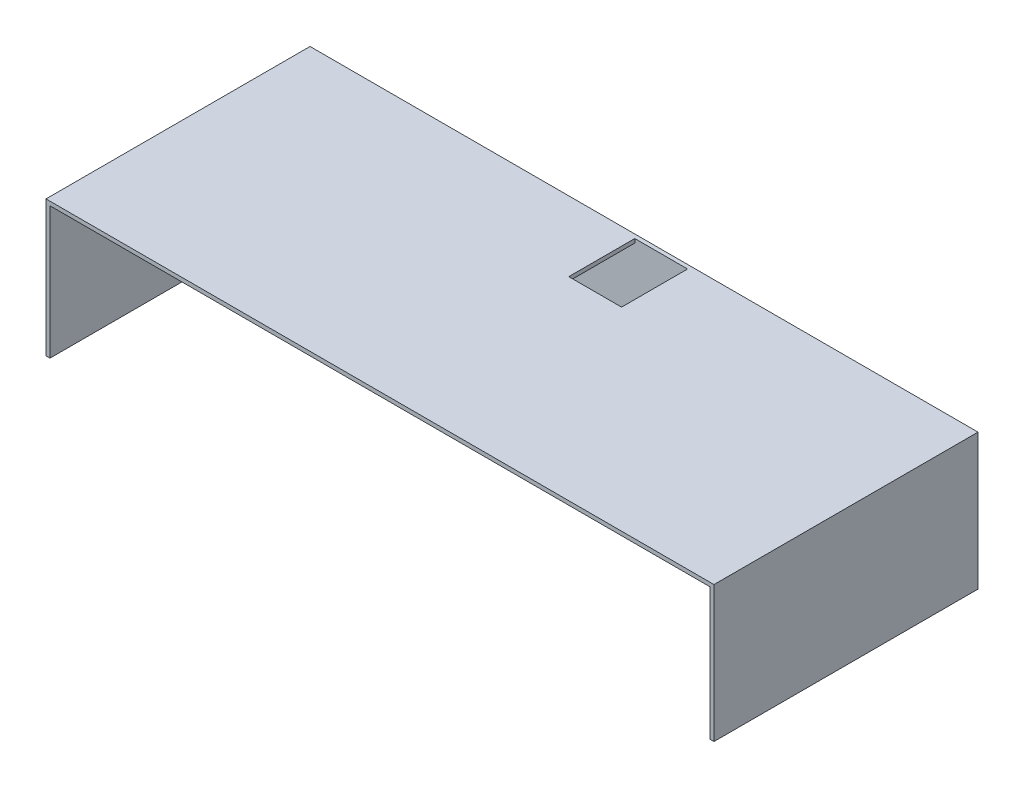
SolidWorks part; units mm, degrees
ref_plane "Front" through (0, 0, 0) normal (0, 0, 1) x (1, 0, 0)
ref_plane "Top" through (0, 0, 0) normal (0, 1, 0) x (1, 0, 0)
ref_plane "Right" through (0, 0, 0) normal (1, 0, 0) x (0, 0, -1)
sketch "草图1" plane through (0, 0, 0) normal (0, 0, 1) x (1, 0, 0)
  line L1 (-25000, 5000) -> (25000, 5000)
  line L2 (-25000, 5000) -> (-25000, -5000)
  line L3 (-25000, -5000) -> (25000, -5000)
  line L4 (25000, 5000) -> (25000, -5000)
  line L5 (-25000, 5000) -> (25000, -5000) construction
  line L6 (-25000, -5000) -> (25000, 5000) construction
  point P0 (0, 0)
extrude "凸台-拉伸1" add sketch "草图1" along normal blind 300
sketch "草图3" plane through (-25000, 0, 0) normal (-1, 0, 0) x (0, 0, 1)
  line L0 (0, 5000) -> (20000, 5000)
  line L1 (0, -5000) -> (20000, -5000)
  line L2 (20000, -5000) -> (20000, 5000)
  line L7 (0, 5000) -> (0, -5000)
  line L8 (0, -5000) -> (300, -5000)
  line L9 (300, -5000) -> (300, 5000)
  line L10 (300, 5000) -> (0, 5000)
  line L11 (0, 5000) -> (0, -5000)
  dimension "D1" = 0
extrude "凸台-拉伸2" add sketch "草图3" along normal blind 300
sketch "草图4" plane through (0, 5000, 0) normal (0, 1, 0) x (1, 0, 0)
  line L0 (-25300, 0) -> (-25300, -20000)
  line L1 (-25300, 0) -> (25000, 0)
  line L2 (25000, 0) -> (25000, -20000)
  line L3 (25000, -20000) -> (-25300, -20000)
extrude "凸台-拉伸3" add sketch "草图4" along normal blind 300
sketch "草图5" plane through (25000, 0, 0) normal (1, 0, 0) x (0, 0, -1)
  line L0 (-20000, 5300) -> (-20000, -5000)
  line L1 (-20000, -5000) -> (0, -5000)
  line L2 (0, -5000) -> (0, 5300)
  line L3 (0, -5000) -> (0, 5300) construction
  line L4 (0, 5300) -> (-20000, 5300)
extrude "凸台-拉伸4" add sketch "草图5" along normal blind 300
sketch "草图6" plane through (0, 5000, 0) normal (0, -1, 0) x (1, 0, 0)
  line L0 (0, 300) -> (-400, 300)
  line L1 (25000, 300) -> (-25000, 300) construction
  line L2 (-25000, 300) -> (25000, 300) construction
  line L3 (0, 300) -> (3600, 300)
  line L4 (3600, 300) -> (3600, 5300)
  line L5 (3600, 5300) -> (-400, 5300)
  line L6 (-400, 5300) -> (-400, 300)
extrude "切除-拉伸1" cut sketch "草图6" against normal blind 300
sketch "草图8" plane through (-400, 0, 0) normal (1, 0, 0) x (0, 0, -1)
  line L1 (-5300, 5150) -> (-300, 5150)
  point P0 (0, 0)
